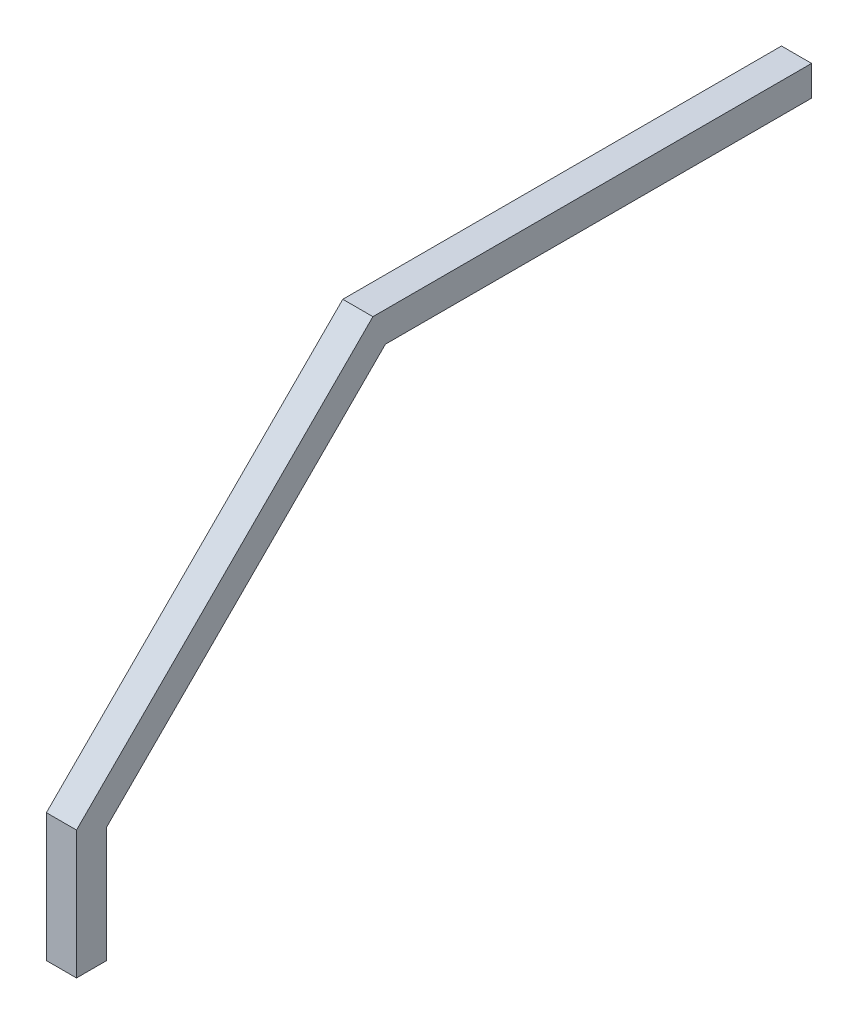
SolidWorks part; units mm, degrees
ref_plane "Front Plane" through (0, 0, 0) normal (0, 0, 1) x (1, 0, 0)
ref_plane "Top Plane" through (0, 0, 0) normal (0, 1, 0) x (1, 0, 0)
ref_plane "Right Plane" through (0, 0, 0) normal (1, 0, 0) x (0, 0, -1)
sketch "Sketch1" plane through (0, 0, 0) normal (1, 0, 0) x (0, 0, -1)
  line L0 (0, 450) -> (250, 700)
  line L1 (250, 700) -> (620, 700)
  line L2 (0, 450) -> (0, 0) construction
  line L3 (0, 450) -> (0, 341.9351)
  line L4 (25.4, 439.479) -> (25.4, 341.9351)
  line L5 (25.4, 439.479) -> (260.521, 674.6)
  line L6 (260.521, 674.6) -> (620, 674.6)
  line L7 (0, 341.9351) -> (25.4, 341.9351)
  line L8 (620, 674.6) -> (620, 700)
  dimension "D1" = 450
  dimension "D2" = 620
  dimension "D3" = 700
  dimension "D4" = 45
  dimension "D5" = 25.4
extrude "Boss-Extrude1" add sketch "Sketch1" along normal blind 25.4
